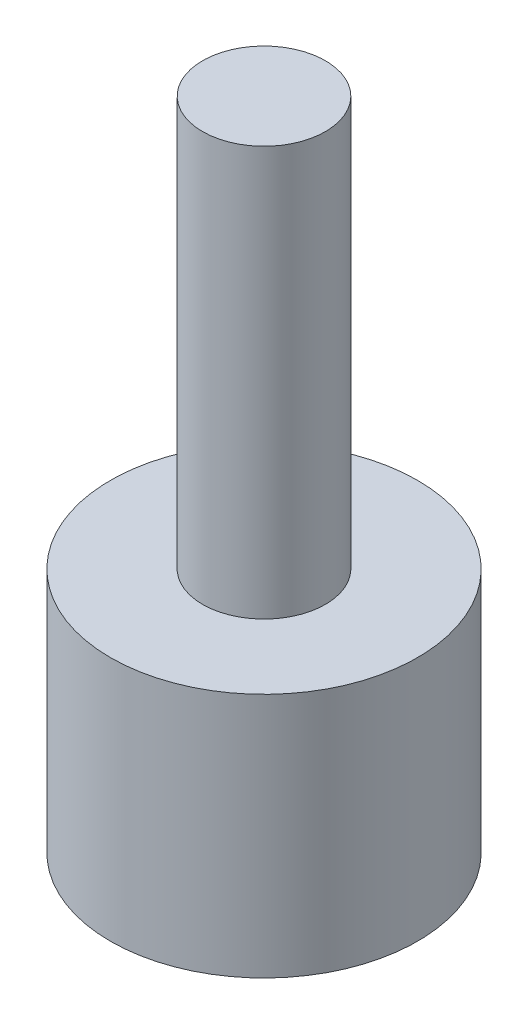
SolidWorks part; units mm, degrees
ref_plane "Front Plane" through (0, 0, 0) normal (0, 0, 1) x (1, 0, 0)
ref_plane "Top Plane" through (0, 0, 0) normal (0, 1, 0) x (1, 0, 0)
ref_plane "Right Plane" through (0, 0, 0) normal (1, 0, 0) x (0, 0, -1)
sketch "Sketch2" plane through (0, 0, 0) normal (0, 1, 0) x (1, 0, 0)
  circle A0 centre (0, 0) radius 3.75
  dimension "D1" = 7.5
extrude "Boss-Extrude1" add sketch "Sketch2" along normal blind 6
sketch "Sketch3" plane through (0, 6, 0) normal (0, 1, 0) x (1, 0, 0)
  circle A0 centre (0, 0) radius 1.5
  dimension "D1" = 3
extrude "Boss-Extrude2" add sketch "Sketch3" along normal blind 10
